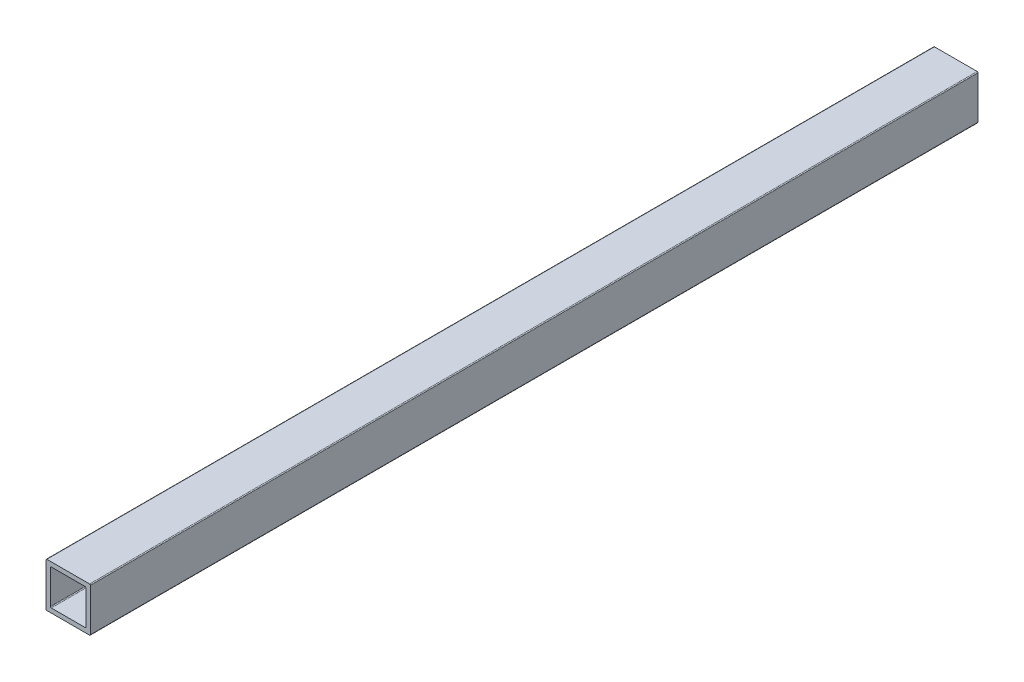
SolidWorks part; units mm, degrees
ref_plane "前基準面" through (0, 0, 0) normal (0, 0, 1) x (1, 0, 0)
ref_plane "上基準面" through (0, 0, 0) normal (0, 1, 0) x (1, 0, 0)
ref_plane "右基準面" through (0, 0, 0) normal (1, 0, 0) x (0, 0, -1)
sketch "草圖1" plane through (0, 0, 0) normal (0, 0, 1) x (1, 0, 0)
  line L1 (-5, 5) -> (5, 5)
  line L2 (-5, 5) -> (-5, -5)
  line L3 (-5, -5) -> (5, -5)
  line L4 (5, 5) -> (5, -5)
  line L5 (-4, 4) -> (4, 4)
  line L6 (-4, 4) -> (-4, -4)
  line L7 (-4, -4) -> (4, -4)
  line L8 (4, 4) -> (4, -4)
  dimension "D1" = 10
  dimension "D2" = 5
  dimension "D3" = 10
  dimension "D4" = 5
  dimension "D5" = 1
  dimension "D6" = 1
  dimension "D7" = 1
  dimension "D8" = 1
extrude "填料-伸長1" add sketch "草圖1" along normal blind 200
fillet "圓角1" radius 0.2 8 edges at (4, 4, 100) (-4, 4, 100) (-5, -5, 100) (4, -4, 100) (5, -5, 100) (-5, 5, 100) (-4, -4, 100) (5, 5, 100)
